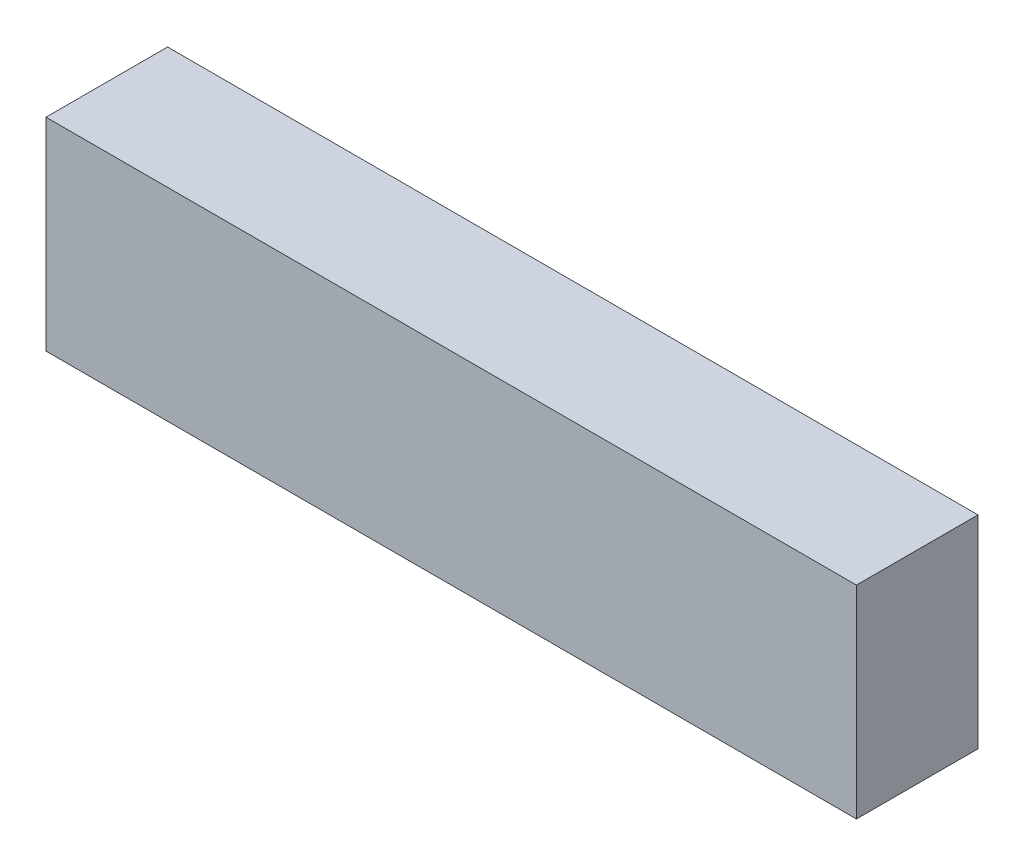
SolidWorks part; units mm, degrees
ref_plane "Front Plane" through (0, 0, 0) normal (0, 0, 1) x (1, 0, 0)
ref_plane "Top Plane" through (0, 0, 0) normal (0, 1, 0) x (1, 0, 0)
ref_plane "Right Plane" through (0, 0, 0) normal (1, 0, 0) x (0, 0, -1)
sketch "Sketch1" plane through (0, 0, 0) normal (0, 0, 1) x (1, 0, 0)
  line L1 (-10, 2.5) -> (10, 2.5)
  line L2 (-10, 2.5) -> (-10, -2.5)
  line L3 (-10, -2.5) -> (10, -2.5)
  line L4 (10, 2.5) -> (10, -2.5)
  line L5 (-10, 2.5) -> (10, -2.5) construction
  line L6 (-10, -2.5) -> (10, 2.5) construction
  point P0 (0, 0)
  dimension "D1" = 5
  dimension "D2" = 20
extrude "Boss-Extrude1" add sketch "Sketch1" along normal blind 3
